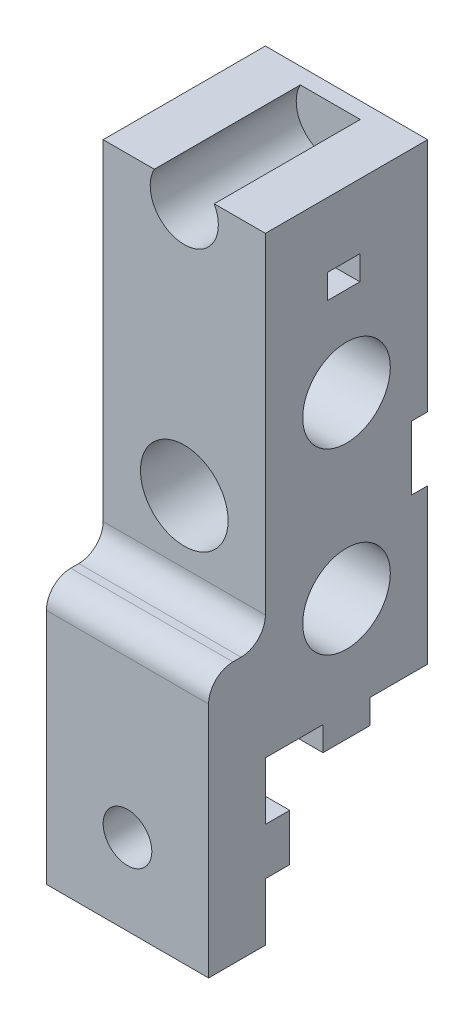
SolidWorks part; units mm, degrees
ref_plane "Front Plane" through (0, 0, 0) normal (0, 0, 1) x (1, 0, 0)
ref_plane "Top Plane" through (0, 0, 0) normal (0, 1, 0) x (1, 0, 0)
ref_plane "Right Plane" through (0, 0, 0) normal (1, 0, 0) x (0, 0, -1)
sketch "Sketch24" plane through (0, 0, 0) normal (1, 0, 0) x (0, 0, -1)
  line L0 (10, -9.1579) -> (10, 46.8421)
  line L1 (2.9, -9.1579) -> (2.9, -12.1579)
  line L2 (-10, 46.8421) -> (-10, -9.1579)
  line L3 (-10, -9.1579) -> (-2.9, -9.1579)
  line L4 (2.9, -12.1579) -> (-2.9, -12.1579)
  line L5 (-2.9, -12.1579) -> (-2.9, -9.1579)
  line L6 (2.9, -9.1579) -> (10, -9.1579)
  line L7 (-10, 46.8421) -> (10, 46.8421)
  line L9 (-2.3533, 38.8421) -> (1.6467, 38.8421)
  line L10 (-2.3533, 38.8421) -> (-2.3533, 35.8421)
  line L11 (-2.3533, 35.8421) -> (1.6467, 35.8421)
  line L12 (1.6467, 38.8421) -> (1.6467, 35.8421)
  line L13 (-2.3533, 38.8421) -> (1.6467, 35.8421) construction
  line L14 (-2.3533, 35.8421) -> (1.6467, 38.8421) construction
  circle A0 centre (0, 24.8421) radius 5.4
  circle A1 centre (0, 2.8421) radius 5.4
  point P2 (-0.3533, 37.3421)
  dimension "D6" = 10.8
  dimension "D1" = 22
  dimension "D2" = 5.8
  dimension "D3" = 3
  dimension "D4" = 7.1
  dimension "D5" = 56
  dimension "D7" = 9.5
  dimension "D8" = 12
extrude "Boss-Extrude1" add sketch "Sketch24" along normal blind 20
sketch "Sketch28" plane through (20, 0, 0) normal (1, 0, 0) x (0, 0, -1)
  line L3 (-10, 3.0921) -> (-10, -29.1579)
  line L4 (-10, 3.0921) -> (-17, 3.0921)
  line L5 (-10, 46.8421) -> (-10, -9.1579) construction
  line L6 (-17, 3.0921) -> (-17, -29.1579)
  line L7 (-17, -29.1579) -> (-10, -29.1579)
extrude "Boss-Extrude2" add sketch "Sketch28" against normal blind 20
sketch "Sketch25" plane through (0, 0, 10) normal (0, 0, 1) x (1, 0, 0)
  line L0 (20, -9.1579) -> (0, -9.1579) construction
  line L1 (0, 13.8421) -> (20, 13.8421) construction
  line L2 (0, 46.8421) -> (0, 3.0921) construction
  line L3 (20, 46.8421) -> (20, 3.0921) construction
  circle A0 centre (10, 13.8421) radius 5.4
  point P10 (10, 13.8421)
  dimension "D1" = 10.8
  dimension "D2" = 23
sketch "Sketch26" plane through (0, 0, 10) normal (0, 0, 1) x (1, 0, 0)
  line L0 (20, -9.1579) -> (0, -9.1579) construction
  line L1 (0, 44.8421) -> (20, 44.8421) construction
  line L2 (0, 46.8421) -> (0, 3.0921) construction
  line L3 (20, 46.8421) -> (20, 3.0921) construction
  circle A0 centre (10, 44.8421) radius 4.2
  point P11 (10, 44.8421)
  dimension "D2" = 8.4
  dimension "D1" = 54
extrude "Cut-Extrude1" cut sketch "Sketch25" against normal blind 20
extrude "Cut-Extrude2" cut sketch "Sketch26" against normal blind 18
sketch "Sketch27" plane through (0, 0, -10) normal (0, 0, -1) x (-1, 0, 0)
  circle A0 centre (-10, 13.8421) radius 10.75
extrude "Cut-Extrude3" cut sketch "Sketch27" against normal blind 2
fillet "Fillet4" radius 3 1 edges at (10, 3.0921, 17)
fillet "Fillet6" radius 3 3 edges
sketch "Sketch31" plane through (0, 0, 17) normal (0, 0, 1) x (1, 0, 0)
  line L0 (0, -29.1579) -> (20, -29.1579) construction
  circle A0 centre (10, -19.1579) radius 3
  dimension "D1" = 10
extrude "Cut-Extrude5" cut sketch "Sketch31" against normal blind 7
sketch "Sketch32" plane through (0, 0, 10) normal (0, 0, -1) x (-1, 0, 0)
  line L0 (0, -29.1579) -> (0, -9.1579) construction
  line L7 (-3, -16.2579) -> (0, -16.2579)
  line L8 (-3, -16.2579) -> (-3, -22.0579)
  line L9 (-3, -22.0579) -> (0, -22.0579)
  line L10 (0, -16.2579) -> (0, -22.0579)
  line L11 (-3, -16.2579) -> (0, -22.0579) construction
  line L12 (-3, -22.0579) -> (0, -16.2579) construction
  line L13 (-20, -29.1579) -> (-20, -9.1579) construction
  line L14 (-17, -16.2579) -> (-20, -16.2579)
  line L15 (-17, -16.2579) -> (-17, -22.0579)
  line L16 (-17, -22.0579) -> (-20, -22.0579)
  line L17 (-20, -16.2579) -> (-20, -22.0579)
  line L18 (-17, -16.2579) -> (-20, -22.0579) construction
  line L19 (-17, -22.0579) -> (-20, -16.2579) construction
  line L20 (-20, -19.1579) -> (0, -19.1579) construction
  point P1 (-1.5, -19.1579)
  point P16 (-18.5, -19.1579)
  dimension "D1" = 3
  dimension "D2" = 5.8
extrude "Boss-Extrude3" add sketch "Sketch32" along normal blind 3
